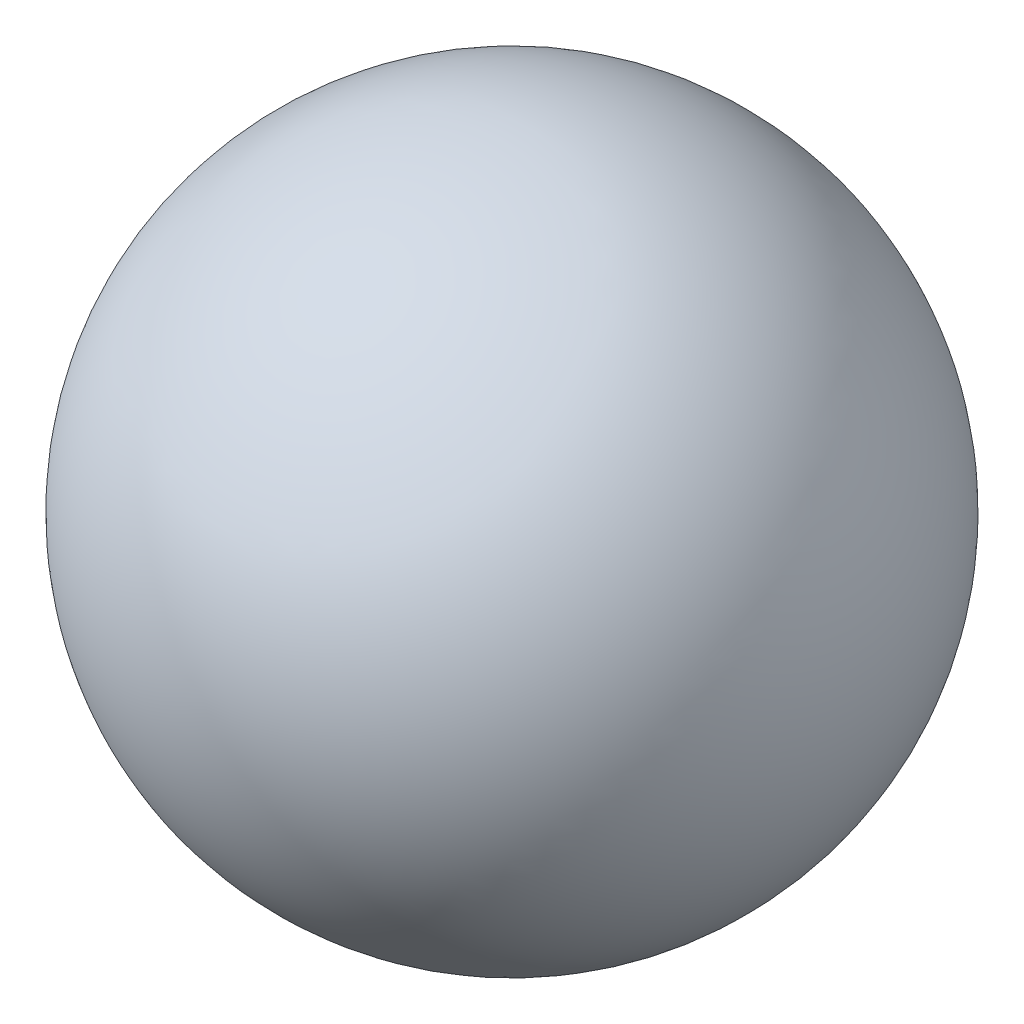
SolidWorks part; units mm, degrees
ref_plane "Front Plane" through (0, 0, 0) normal (0, 0, 1) x (1, 0, 0)
ref_plane "Top Plane" through (0, 0, 0) normal (0, 1, 0) x (1, 0, 0)
ref_plane "Right Plane" through (0, 0, 0) normal (1, 0, 0) x (0, 0, -1)
sketch "Sketch1" plane through (0, 0, 0) normal (0, 1, 0) x (1, 0, 0)
  line L0 (0, 1.5516) -> (0, -1.6436) construction
  line L1 (0, 0.625) -> (0, -0.625)
  line L2 (-1.0123, 0) -> (1.41, 0) construction
  arc A0 (0, -0.625) -> (0, 0.625) centre (0, 0) ccw
  point P1 (0, 0)
  dimension "D1" = 1.25
revolve "Revolve2" add sketch "Sketch1" angle 360 about L0
